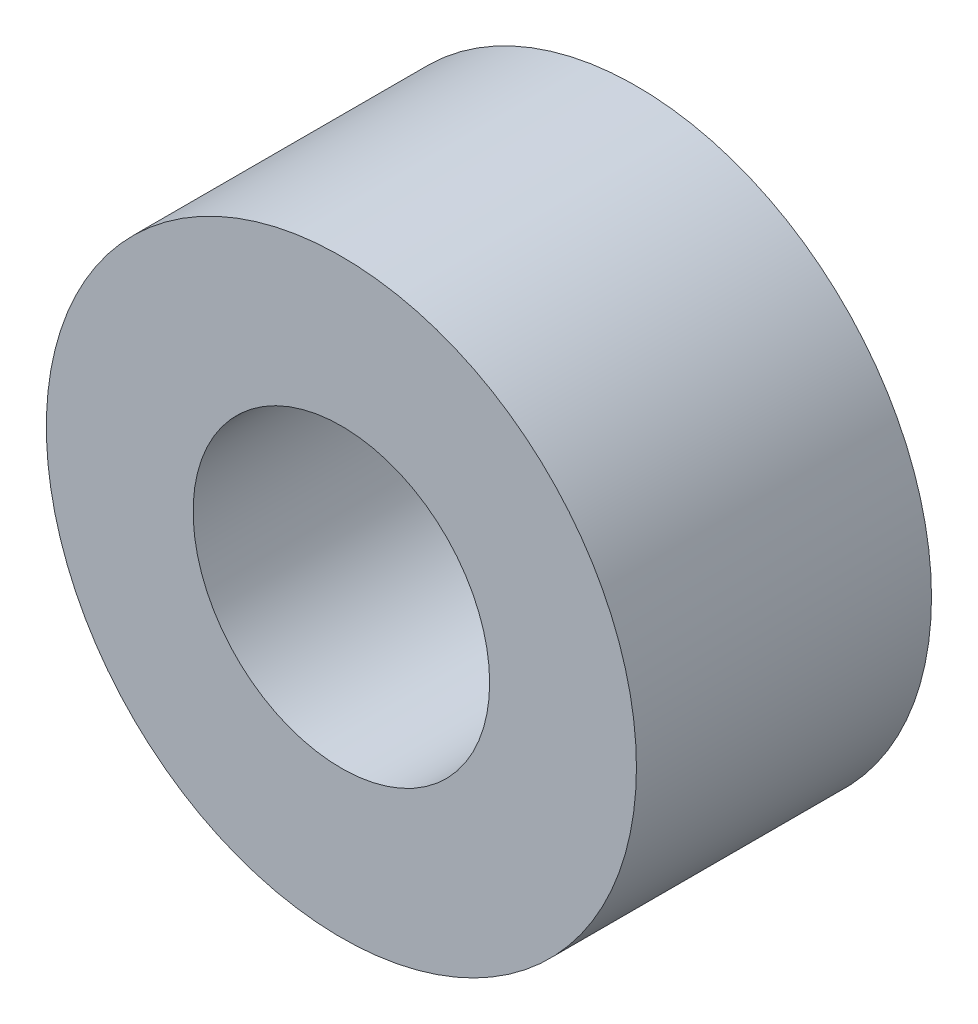
SolidWorks part; units mm, degrees
ref_plane "Front Plane" through (0, 0, 0) normal (0, 0, 1) x (1, 0, 0)
ref_plane "Top Plane" through (0, 0, 0) normal (0, 1, 0) x (1, 0, 0)
ref_plane "Right Plane" through (0, 0, 0) normal (1, 0, 0) x (0, 0, -1)
sketch "Sketch1" plane through (0, 0, 0) normal (0, 0, 1) x (1, 0, 0)
  circle A0 centre (0, 0) radius 10
  dimension "D1" = 20
extrude "Boss-Extrude1" add sketch "Sketch1" along normal blind 10
sketch "Sketch2" plane through (0, 0, 10) normal (0, 0, 1) x (1, 0, 0)
  circle A0 centre (0, 0) radius 5.025
  dimension "D1" = 10.05
extrude "Cut-Extrude1" cut sketch "Sketch2" against normal blind 10
